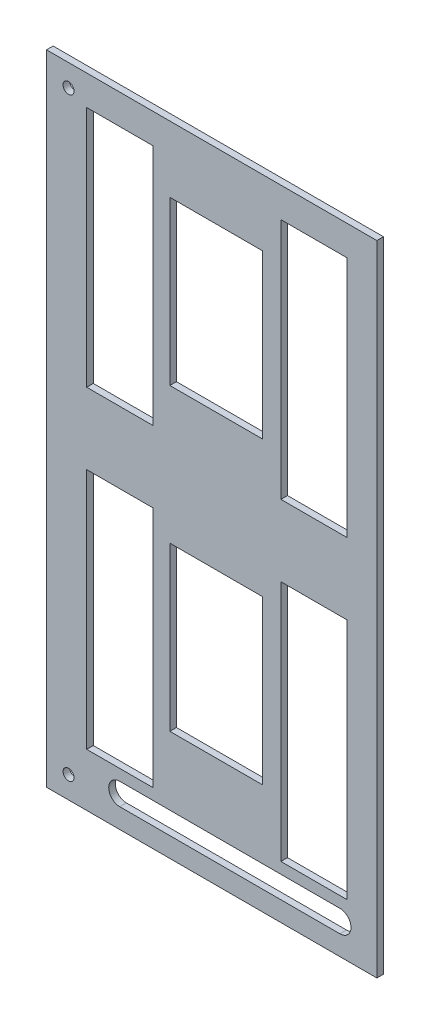
SolidWorks part; units mm, degrees
ref_plane "前视基准面" through (0, 0, 0) normal (0, 0, 1) x (1, 0, 0)
ref_plane "上视基准面" through (0, 0, 0) normal (0, 1, 0) x (1, 0, 0)
ref_plane "右视基准面" through (0, 0, 0) normal (1, 0, 0) x (0, 0, -1)
other "Configuration Table"
sketch "草图2" plane through (0, 0, 0) normal (0, 0, 1) x (1, 0, 0)
  line L1 (-28.1743, 51.6962) -> (121.8257, 51.6962)
  line L2 (-28.1743, 51.6962) -> (-28.1743, -238.3038)
  line L3 (-28.1743, -238.3038) -> (121.8257, -238.3038)
  line L4 (121.8257, 51.6962) -> (121.8257, -238.3038)
  dimension "D1" = 290
  dimension "D2" = 150
extrude "凸台-拉伸1" add sketch "草图2" along normal blind 3
sketch "草图3" plane through (0, 0, 3) normal (0, 0, 1) x (1, 0, 0)
  line L0 (27.8257, 21.6962) -> (69.8257, 21.6962)
  line L1 (27.8257, -114.3038) -> (69.8257, -114.3038)
  line L2 (27.8257, -114.3038) -> (27.8257, -188.3038)
  line L3 (27.8257, -188.3038) -> (69.8257, -188.3038)
  line L4 (69.8257, -114.3038) -> (69.8257, -188.3038)
  line L5 (27.8257, 21.6962) -> (27.8257, -52.3038)
  line L6 (27.8257, -52.3038) -> (69.8257, -52.3038)
  line L7 (69.8257, 21.6962) -> (69.8257, -52.3038)
  line L8 (-28.1743, 51.6962) -> (-28.1743, -238.3038) construction
  line L9 (-28.1743, -238.3038) -> (121.8257, -238.3038) construction
  line L10 (121.8257, 51.6962) -> (-28.1743, 51.6962) construction
  dimension "D1" = 74
  dimension "D2" = 42
  dimension "D3" = 56
  dimension "D4" = 56
  dimension "D5" = 50
  dimension "D6" = 30
  dimension "D7" = 74
  dimension "D8" = 42
extrude "切除-拉伸1" cut sketch "草图3" against normal blind 3 contours L0 L7 L6 L5 | L2 L1 L4 L3
sketch "草图4" plane through (0, 0, 3) normal (0, 0, 1) x (1, 0, 0)
  line L0 (-28.1743, 51.6962) -> (-28.1743, -238.3038) construction
  line L1 (121.8257, 51.6962) -> (-28.1743, 51.6962) construction
  line L2 (-28.1743, -238.3038) -> (121.8257, -238.3038) construction
  circle A0 centre (-18.1743, 41.6962) radius 2.5
  circle A1 centre (-18.1743, -228.3038) radius 2.5
  dimension "D1" = 10
  dimension "D2" = 10
  dimension "D3" = 10
  dimension "D4" = 10
extrude "切除-拉伸2" cut sketch "草图4" against normal blind 3
sketch "草图5" plane through (0, 0, 3) normal (0, 0, 1) x (1, 0, 0)
  line L0 (-9.9317, 38.1275) -> (20.0683, 38.1275)
  line L1 (78.2462, 38.1275) -> (108.2462, 38.1275)
  line L2 (78.2462, 38.1275) -> (78.2462, -71.8725)
  line L3 (78.2462, -71.8725) -> (108.2462, -71.8725)
  line L4 (108.2462, 38.1275) -> (108.2462, -71.8725)
  line L5 (-9.9317, 38.1275) -> (-9.9317, -71.8725)
  line L6 (-9.9317, -71.8725) -> (20.0683, -71.8725)
  line L7 (20.0683, 38.1275) -> (20.0683, -71.8725)
  line L8 (-9.9317, -104.2629) -> (20.0683, -104.2629)
  line L9 (-9.9317, -104.2629) -> (-9.9317, -214.2629)
  line L10 (-9.9317, -214.2629) -> (20.0683, -214.2629)
  line L11 (20.0683, -104.2629) -> (20.0683, -214.2629)
  line L12 (78.2462, -104.2629) -> (108.2462, -104.2629)
  line L13 (78.2462, -104.2629) -> (78.2462, -214.2629)
  line L14 (78.2462, -214.2629) -> (108.2462, -214.2629)
  line L15 (108.2462, -104.2629) -> (108.2462, -214.2629)
  dimension "D1" = 110
  dimension "D2" = 30
extrude "切除-拉伸3" cut sketch "草图5" against normal blind 3
sketch "草图6" plane through (0, 0, 3) normal (0, 0, 1) x (1, 0, 0)
  line L0 (5.0683, -224.3156) -> (105.0683, -224.3156) construction
  line L2 (5.0683, -219.3156) -> (105.0683, -219.3156)
  line L3 (5.0683, -229.3156) -> (105.0683, -229.3156)
  arc A0 (5.0683, -219.3156) -> (5.0683, -229.3156) centre (5.0683, -224.3156) ccw
  arc A1 (105.0683, -229.3156) -> (105.0683, -219.3156) centre (105.0683, -224.3156) ccw
  point P4 (55.0683, -224.3156)
extrude "切除-拉伸4" cut sketch "草图6" against normal blind 3
